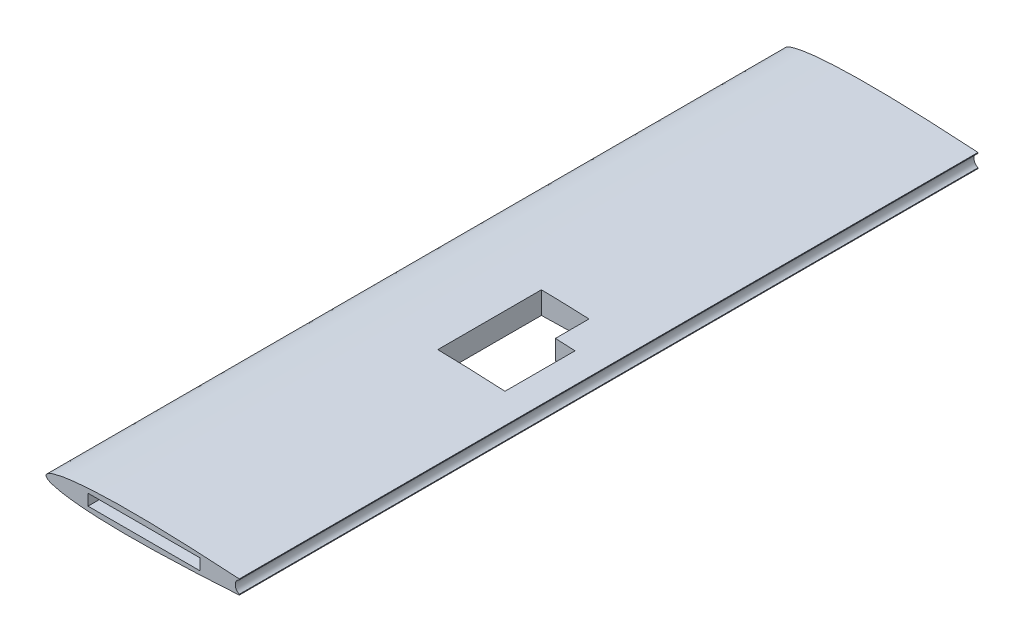
SolidWorks part; units mm, degrees
material "Manual Density from Real Component Stab Orizz. Int Legno"
ref_plane "Piano frontale" through (0, 0, 0) normal (0, 0, 1) x (1, 0, 0)
ref_plane "Piano superiore" through (0, 0, 0) normal (0, 1, 0) x (1, 0, 0)
ref_plane "Piano destro" through (0, 0, 0) normal (1, 0, 0) x (0, 0, -1)
curve "Curva1"
  spline degree 3 poles (100, 0.084, 0) (98.3335, 0.2367, 0) (95.0012, 0.5422, 0) (88.3356, 1.1109, 0) (80.0033, 1.7636, 0) (70.003, 2.4579, 0) (60.0031, 3.0617, 0) (50.003, 3.5521, 0) (40.0026, 3.9029, 0) (31.667, 4.0253, 0) (24.9992, 3.9769, 0) (19.9978, 3.845, 0) (14.9934, 3.5925, 0) (10.8272, 3.2377, 0) (7.4891, 2.814, 0) (4.9936, 2.4037, 0) (2.8496, 1.8679, 0) (1.1654, 1.321, 0) (-0.6646, 0, 0) (1.1654, -1.321, 0) (2.8496, -1.8679, 0) (4.9936, -2.4037, 0) (7.4891, -2.814, 0) (10.8272, -3.2377, 0) (14.9934, -3.5925, 0) (19.9978, -3.845, 0) (24.9992, -3.9769, 0) (31.667, -4.0253, 0) (40.0026, -3.9029, 0) (50.003, -3.5521, 0) (60.0031, -3.0617, 0) (70.003, -2.4579, 0) (80.0033, -1.7636, 0) (88.3356, -1.1109, 0) (95.0012, -0.5422, 0) (98.3335, -0.2367, 0) (100, -0.084, 0) knots 0 0 0 0 0.024876 0.049742 0.099443 0.149112 0.198751 0.248359 0.297937 0.347491 0.372267 0.397051 0.421859 0.446731 0.45922 0.471791 0.48456 0.491195 0.5 0.508805 0.51544 0.528209 0.54078 0.553269 0.578141 0.602949 0.627733 0.652509 0.702063 0.751641 0.801249 0.850888 0.900557 0.950258 0.975124 1 1 1 1
sketch "Schizzo1" plane through (0, 0, 0) normal (0, 0, 1) x (1, 0, 0)
  line L0 (70, 2.443) -> (70, -2.443) construction
  arc A1 (70, 2.443) -> (70, -2.443) centre (70, 0) ccw
  spline S0 degree 3 poles (1029.3323, 4889.466) (420.5539, -80.0474) (258.4436, -13.4031) (88.3356, 1.1109) (80.0033, 1.7636) (70.003, 2.4579) (60.0031, 3.0617) (50.003, 3.5521) (40.0026, 3.9029) (31.667, 4.0253) (24.9992, 3.9769) (19.9978, 3.845) (14.9934, 3.5925) (10.8272, 3.2377) (7.4891, 2.814) (4.9936, 2.4037) (2.8496, 1.8679) (1.1654, 1.321) (-0.6646, 0) (1.1654, -1.321) (2.8496, -1.8679) (4.9936, -2.4037) (7.4891, -2.814) (10.8272, -3.2377) (14.9934, -3.5925) (19.9978, -3.845) (24.9992, -3.9769) (31.667, -4.0253) (40.0026, -3.9029) (50.003, -3.5521) (60.0031, -3.0617) (70.003, -2.4579) (80.0033, -1.7636) (88.3356, -1.1109) (258.4415, 13.4029) (420.5498, 80.0458) (1029.3091, -4889.2764) knots -2.438368 -2.438368 -2.438368 -2.438368 0.024876 0.049742 0.099443 0.149112 0.198751 0.248359 0.297937 0.347491 0.372267 0.397051 0.421859 0.446731 0.45922 0.471791 0.48456 0.491195 0.5 0.508805 0.51544 0.528209 0.54078 0.553269 0.578141 0.602949 0.627733 0.652509 0.702063 0.751641 0.801249 0.850888 0.900557 0.950258 0.975124 3.438336 3.438336 3.438336 3.438336 only from (100, 0.084) to (100, -0.084) construction
  spline S1 degree 3 poles (70, 2.443) (66.6677, 2.6593) (60.0031, 3.0617) (50.003, 3.5521) (40.0026, 3.9029) (31.667, 4.0253) (24.9992, 3.9769) (19.9978, 3.845) (14.9934, 3.5925) (10.8272, 3.2377) (7.4891, 2.814) (4.9936, 2.4037) (2.8496, 1.8679) (1.1654, 1.321) (-0.6646, 0) (1.1654, -1.321) (2.8496, -1.8679) (4.9936, -2.4037) (7.4891, -2.814) (10.8272, -3.2377) (14.9934, -3.5925) (19.9978, -3.845) (24.9992, -3.9769) (31.667, -4.0253) (40.0026, -3.9029) (50.003, -3.5521) (60.0031, -3.0617) (66.6677, -2.6593) (70, -2.443) knots 0.149112 0.149112 0.149112 0.149112 0.198751 0.248359 0.297937 0.347491 0.372267 0.397051 0.421859 0.446731 0.45922 0.471791 0.48456 0.491195 0.5 0.508805 0.51544 0.528209 0.54078 0.553269 0.578141 0.602949 0.627733 0.652509 0.702063 0.751641 0.801249 0.850888 0.850888 0.850888 0.850888
  dimension "D2" = 4.886
extrude "CorpoFoam" add sketch "Schizzo1" along normal blind 263.67
sketch "Schizzo2" plane through (0, 0, 263.67) normal (0, 0, 1) x (1, 0, 0)
  line L0 (72, 0) -> (70, 0) construction
  line L1 (72, 2.5074) -> (69, 2.5074)
  line L2 (72, 2.5074) -> (72, -2.5074)
  line L3 (72, -2.5074) -> (69, -2.5074)
  line L4 (69, 2.5074) -> (69, -2.5074)
  arc A0 (70, 2.443) -> (70, -2.443) centre (70, 0) ccw construction
  spline S0 degree 3 poles (70, 2.443) (66.6677, 2.6593) (60.0031, 3.0617) (50.003, 3.5521) (40.0026, 3.9029) (31.667, 4.0253) (24.9992, 3.9769) (19.9978, 3.845) (14.9934, 3.5925) (10.8272, 3.2377) (7.4891, 2.814) (4.9936, 2.4037) (2.8496, 1.8679) (1.1654, 1.321) (-0.6646, 0) (1.1654, -1.321) (2.8496, -1.8679) (4.9936, -2.4037) (7.4891, -2.814) (10.8272, -3.2377) (14.9934, -3.5925) (19.9978, -3.845) (24.9992, -3.9769) (31.667, -4.0253) (40.0026, -3.9029) (50.003, -3.5521) (60.0031, -3.0617) (66.6677, -2.6593) (70, -2.443) knots 0.149112 0.149112 0.149112 0.149112 0.198751 0.248359 0.297937 0.347491 0.372267 0.397051 0.421859 0.446731 0.45922 0.471791 0.48456 0.491195 0.5 0.508805 0.51544 0.528209 0.54078 0.553269 0.578141 0.602949 0.627733 0.652509 0.702063 0.751641 0.801249 0.850888 0.850888 0.850888 0.850888 construction
  dimension "D1" = 3
  dimension "D2" = 1
extrude "SmussoPosteriore" cut sketch "Schizzo2" against normal through all
sketch "Schizzo3" plane through (0, 0, 263.67) normal (0, 0, 1) x (1, 0, 0)
  circle A0 centre (25, 0) radius 3.25
  dimension "D1" = 6.5
  dimension "D2" = 25
ref_plane "PianoMedio" through (0, 0, 140) normal (0, 0, 1) x (1, 0, 0)
ref_plane "VeroPianoMedio" through (0, 0, 131.835) normal (0, 0, 1) x (1, 0, 0)
sketch "Schizzo5" plane through (0, 0, 0) normal (0, 1, 0) x (1, 0, 0)
  line L0 (52, -133.835) -> (59, -133.835)
  line L1 (35, -158.835) -> (59, -158.835)
  line L2 (35, -158.835) -> (35, -133.835)
  line L3 (35, -133.835) -> (59, -133.835) construction
  line L4 (59, -158.835) -> (59, -133.835)
  line L5 (35, -133.835) -> (52, -133.835) construction
  line L6 (35, -133.835) -> (35, -121.835)
  line L7 (35, -121.835) -> (52, -121.835)
  line L8 (52, -133.835) -> (52, -121.835)
  line L9 (-4.4278, -131.835) -> (4.4278, -131.835) construction
  line L10 (69, -263.67) -> (69, 0) construction
  dimension "D1" = 25
  dimension "D2" = 24
  dimension "D3" = 12
  dimension "D4" = 17
  dimension "D5" = 10
  dimension "D6" = 10
extrude "TaglioServomotore" cut sketch "Schizzo5" against normal through all and the other way through all
ref_plane "PianoAusiliario" through (0, -10, 0) normal (0, 1, 0) x (1, 0, 0)
sketch "Schizzo6" plane through (0, 0, 263.67) normal (0, 0, 1) x (1, 0, 0)
  line L1 (55, 2) -> (15, 2)
  line L2 (55, 2) -> (55, -2)
  line L3 (55, -2) -> (15, -2)
  line L4 (15, 2) -> (15, -2)
  line L5 (55, 2) -> (15, -2) construction
  line L6 (55, -2) -> (15, 2) construction
  point P0 (35, 0)
  dimension "D1" = 4
  dimension "D2" = 40
  dimension "D3" = 15
extrude "TaglioSpinaSinistra" cut sketch "Schizzo6" against normal blind 18
mirror "TaglioSpinaDestra" about plane through (0, 0, 131.835) normal (0, 0, 1) of "TaglioSpinaSinistra"
